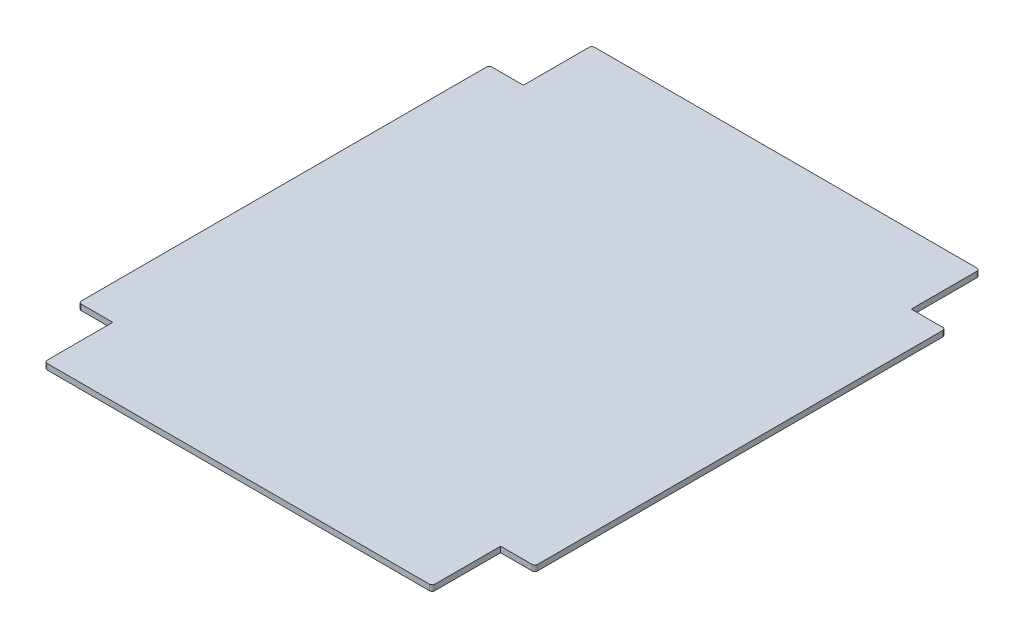
SolidWorks part; units mm, degrees
ref_plane "Front Plane" through (0, 0, 0) normal (0, 0, 1) x (1, 0, 0)
ref_plane "Top Plane" through (0, 0, 0) normal (0, 1, 0) x (1, 0, 0)
ref_plane "Right Plane" through (0, 0, 0) normal (1, 0, 0) x (0, 0, -1)
sketch "Sketch1" plane through (0, 0, 0) normal (0, 1, 0) x (1, 0, 0)
  line L0 (-254, 304.8) -> (-254, 228.6) construction
  line L1 (-215.9, 304.8) -> (215.9, 304.8)
  line L2 (-254, 228.6) -> (-254, -228.6)
  line L3 (-215.9, -304.8) -> (215.9, -304.8)
  line L4 (254, 228.6) -> (254, -228.6)
  line L5 (-215.9, 259.08) -> (215.9, -259.08) construction
  line L6 (-215.9, -259.08) -> (215.9, 259.08) construction
  line L7 (-254, -304.8) -> (-215.9, -304.8) construction
  line L8 (-254, -304.8) -> (-254, -228.6) construction
  line L9 (-254, -228.6) -> (-215.9, -228.6)
  line L10 (-215.9, -304.8) -> (-215.9, -228.6)
  line L11 (-254, 304.8) -> (-215.9, 304.8) construction
  line L12 (-254, 304.8) -> (-254, 228.6) construction
  line L13 (-254, 228.6) -> (-215.9, 228.6)
  line L14 (-215.9, 304.8) -> (-215.9, 228.6)
  line L15 (254, 304.8) -> (215.9, 304.8) construction
  line L16 (254, 304.8) -> (254, 228.6) construction
  line L17 (254, 228.6) -> (215.9, 228.6)
  line L18 (215.9, 304.8) -> (215.9, 228.6)
  line L19 (254, -304.8) -> (215.9, -304.8) construction
  line L20 (254, -304.8) -> (254, -228.6) construction
  line L21 (254, -228.6) -> (215.9, -228.6)
  line L22 (215.9, -304.8) -> (215.9, -228.6)
  line L23 (-254, 304.8) -> (-215.9, 259.08) construction
  line L24 (-254, 304.8) -> (-215.9, 304.8) construction
  line L25 (215.9, 304.8) -> (254, 304.8) construction
  line L26 (215.9, 259.08) -> (254, 304.8) construction
  line L27 (254, 304.8) -> (254, 228.6) construction
  line L28 (254, -228.6) -> (254, -304.8) construction
  line L29 (215.9, -259.08) -> (254, -304.8) construction
  line L30 (215.9, -304.8) -> (254, -304.8) construction
  line L31 (-254, -304.8) -> (-215.9, -304.8) construction
  line L32 (-254, -304.8) -> (-215.9, -259.08) construction
  line L33 (-254, -228.6) -> (-254, -304.8) construction
  point P0 (0, 0)
  dimension "D1" = 609.6
  dimension "D2" = 508
  dimension "D3" = 38.1
  dimension "D4" = 76.2
extrude "Boss-Extrude1" add sketch "Sketch1" along normal blind 6.35
fillet "Fillet2" radius 3.175 8 edges at (-215.9, 3.175, -304.8) (-254, 3.175, -228.6) (215.9, 3.175, -304.8) (254, 3.175, -228.6) (-254, 3.175, 228.6) (-215.9, 3.175, 304.8) (215.9, 3.175, 304.8) (254, 3.175, 228.6)
